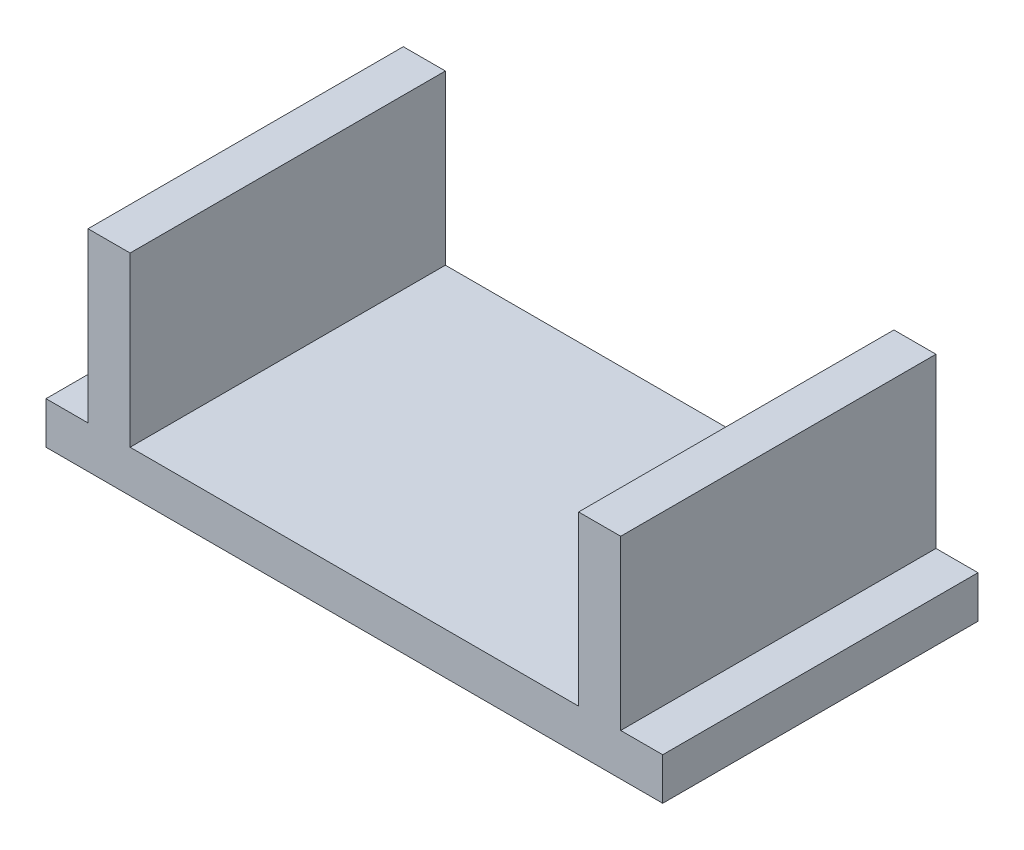
SolidWorks part; units mm, degrees
ref_plane "Front Plane" through (0, 0, 0) normal (0, 0, 1) x (1, 0, 0)
ref_plane "Top Plane" through (0, 0, 0) normal (0, 1, 0) x (1, 0, 0)
ref_plane "Right Plane" through (0, 0, 0) normal (1, 0, 0) x (0, 0, -1)
ref_plane "Plane_zm35_71" through (0, 0, -35.71) normal (0, 0, 1) x (1, 0, 0)
sketch "Sketch1" plane through (0, 0, -35.71) normal (0, 0, 1) x (1, 0, 0)
  line L1 (-69.85, 0) -> (69.85, 0)
  line L2 (-69.85, 0) -> (-69.85, 9.53)
  line L3 (-69.85, 9.53) -> (69.85, 9.53)
  line L4 (69.85, 0) -> (69.85, 9.53)
extrude "Block1" add sketch "Sketch1" along normal blind 71.42
sketch "Sketch2" plane through (0, 0, -35.71) normal (0, 0, 1) x (1, 0, 0)
  line L1 (-60.33, 9.53) -> (-50.8, 9.53)
  line L2 (-60.33, 9.53) -> (-60.33, 47.63)
  line L3 (-60.33, 47.63) -> (-50.8, 47.63)
  line L4 (-50.8, 9.53) -> (-50.8, 47.63)
extrude "Block2" add sketch "Sketch2" along normal blind 71.42
sketch "Sketch3" plane through (0, 0, -35.71) normal (0, 0, 1) x (1, 0, 0)
  line L1 (50.8, 9.53) -> (60.33, 9.53)
  line L2 (50.8, 9.53) -> (50.8, 47.63)
  line L3 (50.8, 47.63) -> (60.33, 47.63)
  line L4 (60.33, 9.53) -> (60.33, 47.63)
extrude "Block3" add sketch "Sketch3" along normal blind 71.42
